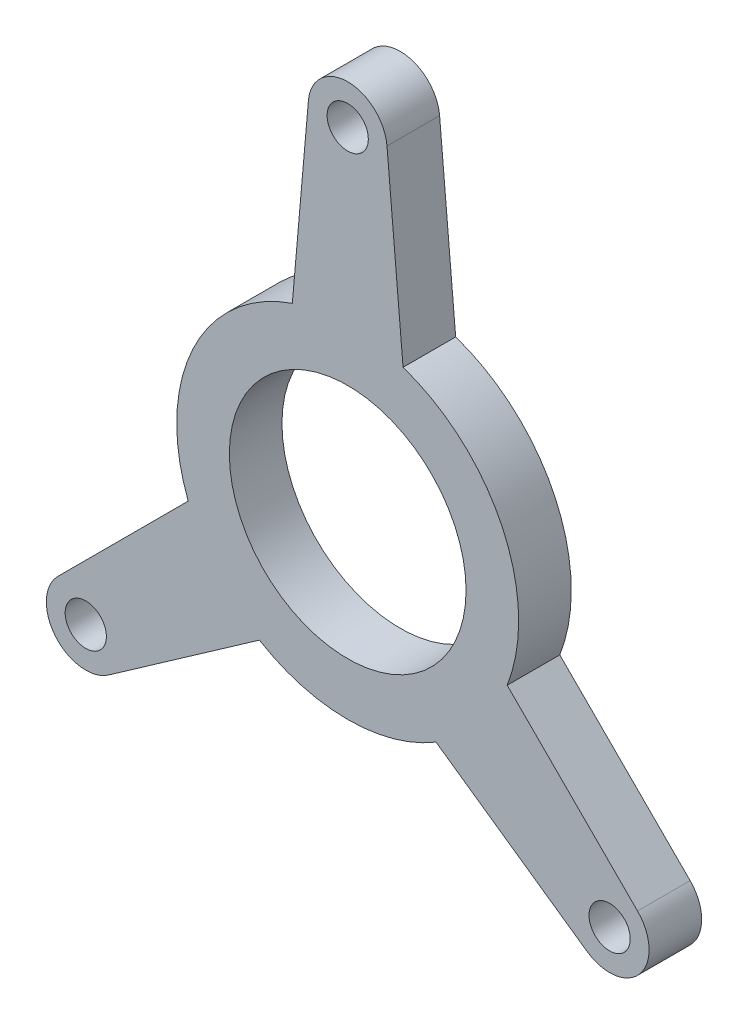
SolidWorks part; units mm, degrees
material "6061-T6 (SS)"
ref_plane "Front Plane" through (0, 0, 0) normal (0, 0, 1) x (1, 0, 0)
ref_plane "Top Plane" through (0, 0, 0) normal (0, 1, 0) x (1, 0, 0)
ref_plane "Right Plane" through (0, 0, 0) normal (1, 0, 0) x (0, 0, -1)
sketch "Sketch1" plane through (0, 0, 0) normal (0, 0, 1) x (1, 0, 0)
  line L0 (0, 0) -> (0, 41.275) construction
  line L1 (0, 0) -> (31.6185, -26.5311) construction
  line L2 (0, 0) -> (-31.6185, -26.5311) construction
  line L3 (-4.7444, 41.6901) -> (-6.6835, 19.5253)
  line L4 (4.7444, 41.6901) -> (6.6835, 19.5253)
  line L5 (34.9861, -23.1635) -> (19.2533, -7.4307)
  line L6 (28.8868, -30.4323) -> (10.6611, -17.6705)
  line L7 (-28.8868, -30.4323) -> (-10.6611, -17.6705)
  line L8 (-19.2533, -7.4307) -> (-34.9861, -23.1635)
  circle A0 centre (31.6185, -26.5311) radius 4.7625
  circle A1 centre (0, 41.275) radius 4.7625
  circle A2 centre (-31.6185, -26.5311) radius 4.7625
  circle A3 centre (31.6185, -26.5311) radius 2.4892
  circle A4 centre (-31.6185, -26.5311) radius 2.4892
  circle A5 centre (0, 41.275) radius 2.4892
  circle A6 centre (0, 0) radius 14.2875
  circle A7 centre (0, 0) radius 20.6375
  dimension "D1" = 9.525
  dimension "D4" = 4.9784
  dimension "D13" = 6.35
  dimension "D14" = 28.575
  dimension "D2" = 41.275
  dimension "D5" = 130
  dimension "D6" = 130
  dimension "D7" = 5
  dimension "D8" = 5
  dimension "D9" = 5
  dimension "D10" = 5
  dimension "D11" = 5
  dimension "D12" = 5
extrude "Boss-Extrude1" add sketch "Sketch1" along normal mid plane 6.35 contours A7 A6 | A7 L4 A1 L3 | A7 L6 A0 L5 | A7 L8 A2 L7 | A2 A4 | A1 A5 | A0 A3
